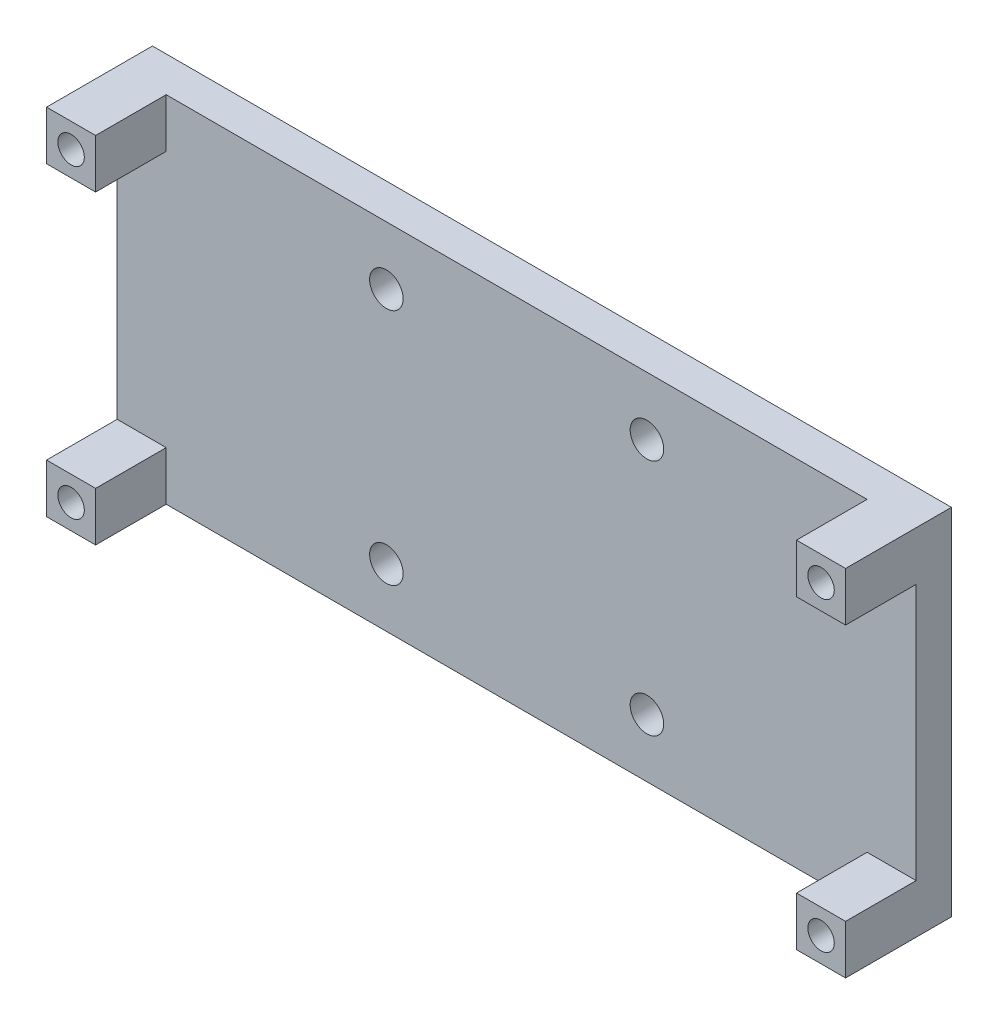
SolidWorks part; units mm, degrees
ref_plane "Front Plane" through (0, 0, 0) normal (0, 0, 1) x (1, 0, 0)
ref_plane "Top Plane" through (0, 0, 0) normal (0, 1, 0) x (1, 0, 0)
ref_plane "Right Plane" through (0, 0, 0) normal (1, 0, 0) x (0, 0, -1)
sketch "Sketch2" plane through (0, 0, 0) normal (0, 0, 1) x (1, 0, 0)
  line L0 (36.99, 25.1) -> (-8.29, 25.1)
  line L1 (-8.29, 25.1) -> (-8.29, 5)
  line L2 (-8.29, 5) -> (3.35, 5)
  line L3 (14.35, 25.1) -> (14.35, 5) construction
  line L4 (25.35, 25.1) -> (3.35, 25.1) construction
  line L5 (3.35, 15.05) -> (25.35, 15.05) construction
  line L6 (3.35, 5) -> (25.35, 5)
  line L7 (36.99, 5) -> (25.35, 5)
  line L8 (3.35, 25.1) -> (3.35, 5) construction
  line L9 (25.35, 5) -> (3.35, 5) construction
  line L10 (25.35, 25.1) -> (25.35, 5) construction
  line L11 (3.35, 5) -> (25.35, 25.1) construction
  line L12 (36.99, 25.1) -> (36.99, 5)
  circle A0 centre (6.9673, 8.3049) radius 0.95
  circle A1 centre (6.9673, 21.7951) radius 0.95
  circle A2 centre (21.7327, 8.3049) radius 0.95
  circle A3 centre (21.7327, 21.7951) radius 0.95
  circle A4 centre (35.6, 23.71) radius 0.75 construction
  circle A5 centre (35.6, 6.39) radius 0.75 construction
  circle A6 centre (-6.9, 6.39) radius 0.75 construction
  circle A7 centre (-6.9, 23.71) radius 0.75 construction
  circle A8 centre (35.6, 23.71) radius 0.75
  circle A9 centre (35.6, 6.39) radius 0.75
  circle A10 centre (-6.9, 6.39) radius 0.75
  circle A11 centre (-6.9, 23.71) radius 0.75
  point P0 (14.35, 15.05)
  point P21 (3.35, 15.05)
  point P22 (14.35, 5)
  point P23 (14.35, 25.1)
  dimension "D3" = 1.9
  dimension "D1" = 11
  dimension "D2" = 10
  dimension "D4" = 20.1
  dimension "D5" = 22.64
extrude "Boss-Extrude1" add sketch "Sketch2" along normal blind 2
sketch "Sketch4" plane through (0, 0, 2) normal (0, 0, 1) x (1, 0, 0)
  line L0 (-8.29, 25.1) -> (-8.29, 5) construction
  line L1 (-5.51, 22.32) -> (-8.29, 22.32)
  line L2 (36.99, 25.1) -> (-8.29, 25.1) construction
  line L3 (-8.29, 25.1) -> (-5.51, 22.32) construction
  line L4 (-6.9, 23.71) -> (-2.3638, 28.2462) construction
  line L5 (-5.51, 22.32) -> (-5.51, 25.1)
  line L6 (-5.51, 25.1) -> (-8.29, 25.1)
  line L7 (-8.29, 25.1) -> (-8.29, 22.32)
  line L8 (14.35, 25.1) -> (14.35, 5) construction
  line L9 (-8.29, 5) -> (36.99, 5) construction
  line L10 (-8.29, 15.05) -> (36.99, 15.05) construction
  line L11 (36.99, 5) -> (36.99, 25.1) construction
  line L12 (36.99, 25.1) -> (34.21, 22.32) construction
  line L13 (36.99, 25.1) -> (36.99, 22.32)
  line L14 (34.21, 25.1) -> (36.99, 25.1)
  line L15 (34.21, 22.32) -> (34.21, 25.1)
  line L16 (34.21, 22.32) -> (36.99, 22.32)
  line L17 (36.99, 5) -> (34.21, 7.78) construction
  line L18 (-8.29, 5) -> (-5.51, 7.78) construction
  line L19 (34.21, 7.78) -> (36.99, 7.78)
  line L20 (34.21, 7.78) -> (34.21, 5)
  line L21 (34.21, 5) -> (36.99, 5)
  line L22 (36.99, 5) -> (36.99, 7.78)
  line L23 (-8.29, 5) -> (-8.29, 7.78)
  line L24 (-5.51, 5) -> (-8.29, 5)
  line L25 (-5.51, 7.78) -> (-5.51, 5)
  line L26 (-5.51, 7.78) -> (-8.29, 7.78)
  circle A0 centre (-6.9, 23.71) radius 0.75
  circle A1 centre (35.6, 23.71) radius 0.75
  circle A2 centre (35.6, 6.39) radius 0.75
  circle A3 centre (-6.9, 6.39) radius 0.75
  dimension "D1" = 1.5
  dimension "D3" = 2.14
  dimension "D2" = 2.14
extrude "Boss-Extrude2" add sketch "Sketch4" along normal blind 4
